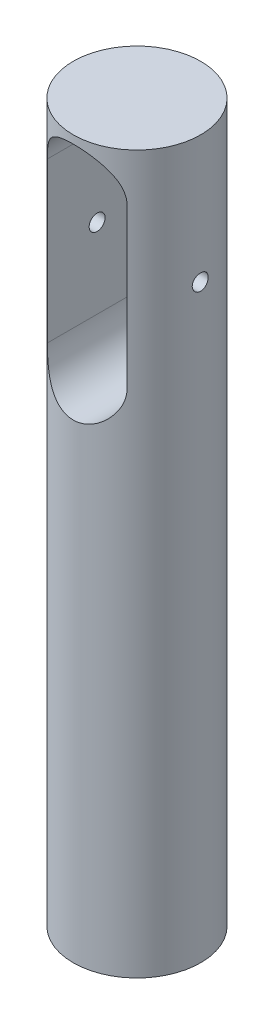
SolidWorks part; units mm, degrees
ref_plane "Front Plane" through (0, 0, 0) normal (0, 0, 1) x (1, 0, 0)
ref_plane "Top Plane" through (0, 0, 0) normal (0, 1, 0) x (1, 0, 0)
ref_plane "Right Plane" through (0, 0, 0) normal (1, 0, 0) x (0, 0, -1)
sketch "Sketch1" plane through (0, 0, 0) normal (0, 1, 0) x (1, 0, 0)
  circle A0 centre (0, 0) radius 40
  dimension "D1" = 80
extrude "Boss-Extrude1" add sketch "Sketch1" along normal blind 450
sketch "Sketch2" plane through (0, 0, 0) normal (0, 0, 1) x (1, 0, 0)
  line L0 (40, 450) -> (-40, 450) construction
  line L2 (25, 420) -> (25, 320)
  line L4 (-25, 420) -> (-25, 320)
  line L5 (25, 420) -> (-25, 320) construction
  line L6 (25, 320) -> (-25, 420) construction
  arc A0 (25, 420) -> (-25, 420) centre (0, 420) ccw
  arc A1 (25, 320) -> (-25, 320) centre (0, 320) cw
  point P0 (0, 370)
  dimension "D1" = 80
  dimension "D2" = 50
  dimension "D3" = 100
extrude "Cut-Extrude1" cut sketch "Sketch2" against normal through all both and the other way through all
sketch "Sketch3" plane through (0, 0, 0) normal (1, 0, 0) x (0, 0, -1)
  circle A0 centre (0, 370) radius 5
  dimension "D1" = 10
extrude "Cut-Extrude2" cut sketch "Sketch3" against normal through all both and the other way through all
